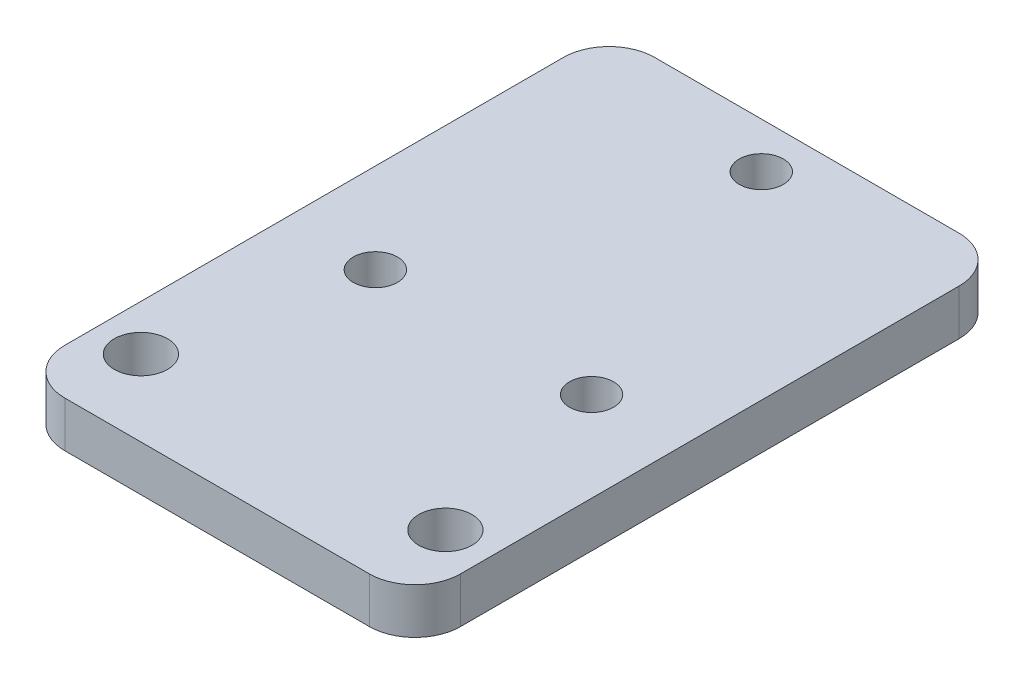
SolidWorks part; units mm, degrees
material "ABS"
ref_plane "前视基准面" through (0, 0, 0) normal (0, 0, 1) x (1, 0, 0)
ref_plane "上视基准面" through (0, 0, 0) normal (0, 1, 0) x (1, 0, 0)
ref_plane "右视基准面" through (0, 0, 0) normal (1, 0, 0) x (0, 0, -1)
other "Configuration Table"
sketch "草图1" plane through (0, 0, 0) normal (0, 1, 0) x (1, 0, 0)
  line L0 (0, 0) -> (0, -7.5) construction
  line L1 (-10, -7.5) -> (10, -7.5) construction
  line L2 (0, 5) -> (0, 23.25) construction
  line L3 (-13, 22.5) -> (13, 22.5) construction
  line L4 (-13, 22.5) -> (-13, -12.5)
  line L5 (-13, -12.5) -> (13, -12.5)
  line L6 (13, 22.5) -> (13, -12.5)
  line L7 (-13, 22.5) -> (13, -12.5) construction
  line L8 (-13, -12.5) -> (13, 22.5) construction
  line L9 (-13, 0) -> (13, 0) construction
  line L10 (-13, 22.5) -> (-13, 26.25)
  line L11 (-13, 26.25) -> (13, 26.25)
  line L12 (13, 26.25) -> (13, 22.5)
  line L13 (-7.1, 5) -> (7.1, 5) construction
  circle A0 centre (-10, -7.5) radius 1.75
  circle A1 centre (10, -7.5) radius 1.75
  circle A2 centre (0, 23.25) radius 1.45
  circle A3 centre (-7.1, 5) radius 1.45
  circle A4 centre (7.1, 5) radius 1.45
  point P6 (0, -7.5)
  point P8 (0, 5)
  point P17 (0, 0)
  point P24 (0, 5)
  dimension "D3" = 3.5
  dimension "D5" = 5
  dimension "D10" = 2.9
  dimension "D1" = 7.5
  dimension "D2" = 20
  dimension "D4" = 3
  dimension "D6" = 5
  dimension "D7" = 18.25
  dimension "D8" = 3
  dimension "D9" = 14.2
extrude "凸台-拉伸1" add sketch "草图1" along normal blind 3
fillet "圆角1" radius 3 4 edges at (13, 1.5, 12.5) (-13, 1.5, -26.25) (13, 1.5, -26.25) (-13, 1.5, 12.5)
sketch "草图3" plane through (0, 0, 0) normal (1, 0, 0) x (0, 0, -1)
  line L0 (0, 0) -> (0, -10)
  line L1 (0, -10) -> (15.25, 0)
  line L2 (5, 0) -> (23.25, 0) construction
  line L3 (15.25, 0) -> (0, 0)
  dimension "D1" = 8
  dimension "D2" = 10
extrude "凸台-拉伸2" add sketch "草图3" along normal mid plane 5
fillet "圆角2" radius 1.5 3 edges at (-2.5, 0, -7.625) (0, 0, -15.25) (2.5, 0, -7.625)
fillet "圆角3" radius 1 1 edges at (0, -10, 0)
